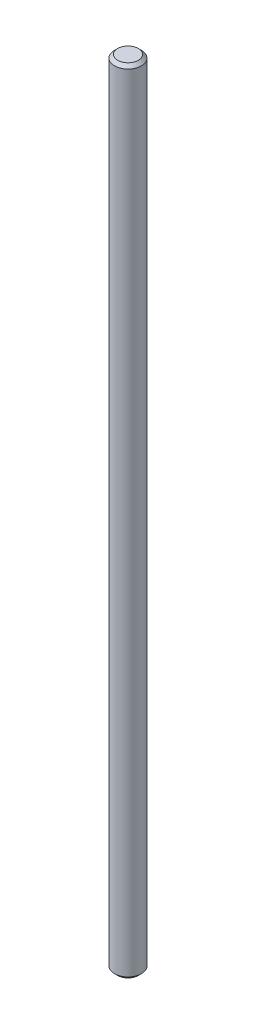
SolidWorks part; units mm, degrees
material "AÇO 1020"
ref_plane "Front Plane" through (0, 0, 0) normal (0, 0, 1) x (1, 0, 0)
ref_plane "Top Plane" through (0, 0, 0) normal (0, 1, 0) x (1, 0, 0)
ref_plane "Right Plane" through (0, 0, 0) normal (1, 0, 0) x (0, 0, -1)
sketch "Sketch1" plane through (0, 0, 0) normal (0, 1, 0) x (1, 0, 0)
  circle A0 centre (0, 0) radius 4.25
  dimension "D1" = 8.5
extrude "Extrude1" add sketch "Sketch1" along normal blind 250
cosmetic thread "Cosmetic Thread1" parameters "D2"=6.619
chamfer "Chamfer1" distance 1 angle 45 1 edges at (0, 250, 4.25)
chamfer "Chamfer2" distance 1 angle 45 1 edges at (0, 0, 4.25)
